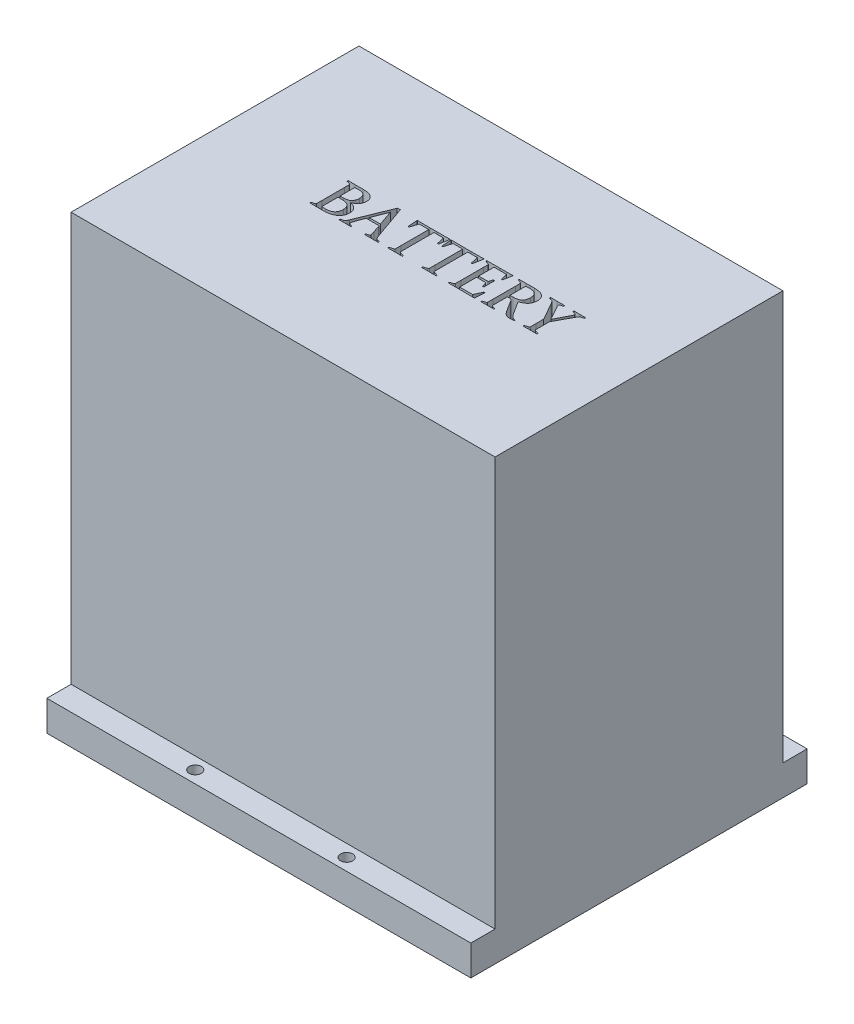
SolidWorks part; units mm, degrees
ref_plane "Front Plane" through (0, 0, 0) normal (0, 0, 1) x (1, 0, 0)
ref_plane "Top Plane" through (0, 0, 0) normal (0, 1, 0) x (1, 0, 0)
ref_plane "Right Plane" through (0, 0, 0) normal (1, 0, 0) x (0, 0, -1)
sketch "Sketch1" plane through (0, 0, 0) normal (0, 1, 0) x (1, 0, 0)
  line L1 (-104.5249, 1.7342) -> (35.4751, 1.7342)
  line L2 (-104.5249, 1.7342) -> (-104.5249, -93.3258)
  line L3 (-104.5249, -93.3258) -> (35.4751, -93.3258)
  line L4 (35.4751, 1.7342) -> (35.4751, -93.3258)
  dimension "D1" = 95.06
  dimension "D2" = 140
extrude "Boss-Extrude1" add sketch "Sketch1" along normal blind 135
sketch "Sketch3" plane through (0, 135, 0) normal (0, 1, 0) x (1, 0, 0)
  text T0 "BATTERY" font "Constantia" height in points 48
extrude "Cut-Extrude1" cut sketch "Sketch3" against normal blind 10
sketch "Sketch5" plane through (0, 0, 0) normal (0, -1, 0) x (1, 0, 0)
  line L0 (35.4751, 93.3258) -> (35.4751, -1.7342) construction
  line L1 (-104.5249, 101.3258) -> (35.4751, 101.3258)
  line L2 (-104.5249, 101.3258) -> (-104.5249, -9.7342)
  line L3 (-104.5249, -9.7342) -> (35.4751, -9.7342)
  line L4 (35.4751, 101.3258) -> (35.4751, -9.7342)
  line L5 (-104.5249, -1.7342) -> (-104.5249, 93.3258) construction
  line L6 (-104.5249, 93.3258) -> (35.4751, 93.3258) construction
  line L7 (35.4751, -1.7342) -> (-104.5249, -1.7342) construction
  circle A0 centre (-59.5249, 97.3258) radius 2
  circle A1 centre (-9.5249, 97.3258) radius 2
  circle A4 centre (-59.5249, -5.7342) radius 1.1945
  circle A5 centre (-9.5249, -5.7342) radius 1.3932
  dimension "D5" = 4
  dimension "D6" = 4
  dimension "D7" = 103.06
  dimension "D1" = 0
  dimension "D2" = 0
  dimension "D3" = 8
  dimension "D4" = 8
  dimension "D9" = 50
  dimension "D10" = 50
extrude "Boss-Extrude2" add sketch "Sketch5" along normal blind 10
sketch "Sketch6" plane through (0, -10, 0) normal (0, -1, 0) x (1, 0, 0)
  circle A0 centre (-59.5249, 97.3258) radius 2
  circle A1 centre (-59.5249, -5.7342) radius 2
  circle A3 centre (-9.5249, -5.7342) radius 2
extrude "Cut-Extrude2" cut sketch "Sketch6" against normal through all
equation "\"3.94inch\"=10"
